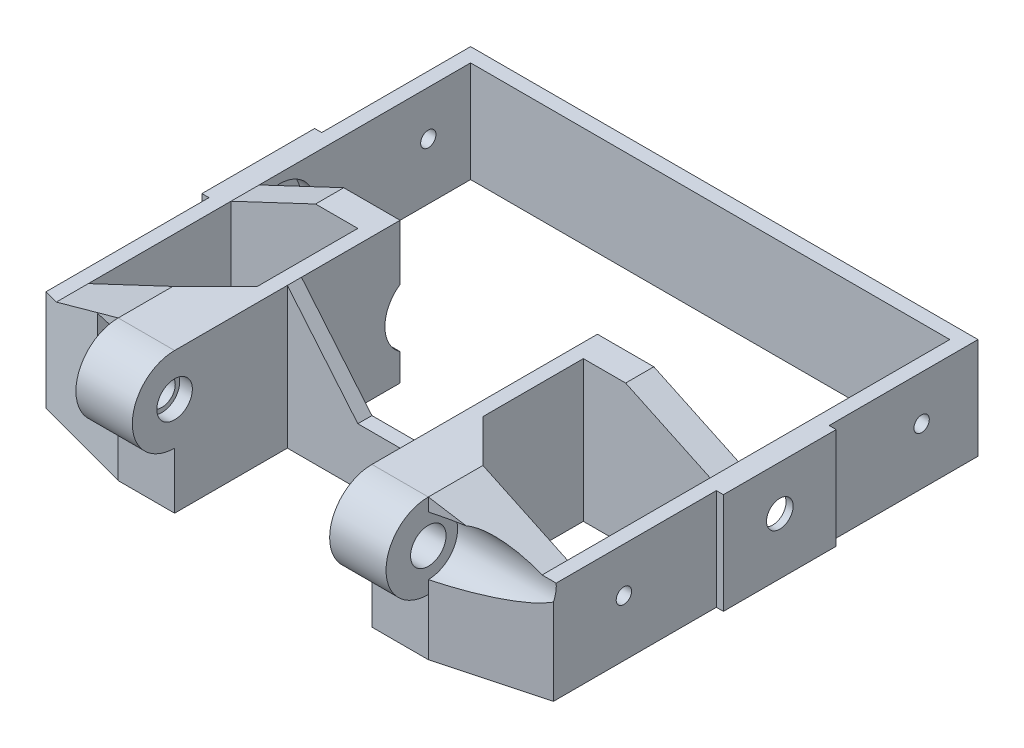
SolidWorks part; units mm, degrees
material "ABS"
ref_plane "Front Plane" through (0, 0, 0) normal (0, 0, 1) x (1, 0, 0)
ref_plane "Top Plane" through (0, 0, 0) normal (0, 1, 0) x (1, 0, 0)
ref_plane "Right Plane" through (0, 0, 0) normal (1, 0, 0) x (0, 0, -1)
sketch "Sketch1" plane through (0, 0, 0) normal (0, 0, 1) x (1, 0, 0)
  line L0 (-22.225, 0) -> (22.225, 0) construction
  line L1 (-22.225, 0) -> (-34.925, 0)
  line L2 (-22.225, 0) -> (-22.225, 9.525)
  line L3 (-22.225, 9.525) -> (-34.925, 9.525)
  line L4 (-34.925, 0) -> (-34.925, 9.525)
  line L5 (22.225, 0) -> (34.925, 0)
  line L6 (22.225, 0) -> (22.225, 9.525)
  line L7 (22.225, 9.525) -> (34.925, 9.525)
  line L8 (34.925, 0) -> (34.925, 9.525)
  dimension "D1" = 44.45
  dimension "D2" = 9.525
  dimension "D3" = 12.7
revolve "Revolve1" add sketch "Sketch1" angle 360 about L0
sketch "Sketch2" plane through (0, 0, 0) normal (0, 1, 0) x (1, 0, 0)
  line L1 (-34.925, 0) -> (-57.15, 5.9552)
  line L2 (-34.925, 9.525) -> (-34.925, -9.525) construction
  line L3 (-57.15, 5.9552) -> (-57.15, 101.6)
  line L4 (-57.15, 101.6) -> (57.15, 101.6)
  line L5 (57.15, 101.6) -> (57.15, 5.9552)
  line L6 (57.15, 5.9552) -> (34.925, 0)
  line L7 (34.925, -9.525) -> (34.925, 9.525) construction
  line L8 (34.925, 0) -> (22.225, 0)
  line L9 (22.225, 9.525) -> (22.225, -9.525) construction
  line L10 (22.225, 0) -> (22.225, 25.4)
  line L11 (22.225, 25.4) -> (-22.225, 25.4)
  line L12 (-22.225, 25.4) -> (-22.225, 0)
  line L13 (-22.225, -9.525) -> (-22.225, 9.525) construction
  line L14 (-22.225, 0) -> (-34.925, 0)
  line L15 (-22.225, 50.8) -> (-53.975, 50.8)
  line L16 (-22.225, 28.575) -> (22.225, 28.575)
  line L17 (-22.225, 28.575) -> (-22.225, 98.425)
  line L18 (-22.225, 98.425) -> (22.225, 98.425)
  line L19 (22.225, 28.575) -> (22.225, 98.425)
  line L20 (-53.975, 98.425) -> (-25.4, 98.425)
  line L21 (-53.975, 98.425) -> (-53.975, 12.3052)
  line L22 (-53.975, 12.3052) -> (-25.4, 12.3052)
  line L23 (-25.4, 98.425) -> (-25.4, 12.3052)
  line L24 (25.4, 98.425) -> (53.975, 98.425)
  line L25 (25.4, 98.425) -> (25.4, 12.3052)
  line L26 (25.4, 12.3052) -> (53.975, 12.3052)
  line L27 (53.975, 98.425) -> (53.975, 12.3052)
  line L28 (-25.4, 44.45) -> (-53.975, 44.45)
  line L29 (22.225, 50.8) -> (53.975, 50.8)
  line L30 (25.4, 44.45) -> (53.975, 44.45)
  line L31 (-25.4, 98.425) -> (-22.225, 98.425)
  line L32 (22.225, 98.425) -> (25.4, 98.425)
  line L33 (25.4, 98.425) -> (23.8524, 98.3686)
  point P24 (-28.575, 0)
  dimension "D1" = 25.4
  dimension "D2" = 101.6
  dimension "D3" = 75
  dimension "D4" = 114.3
  dimension "D5" = 3.175
  dimension "D6" = 3.175
  dimension "D7" = 3.175
  dimension "D8" = 3.175
  dimension "D9" = 3.175
  dimension "D10" = 6.35
  dimension "D11" = 6.35
  dimension "D12" = 47.625
extrude "Boss-Extrude1" add sketch "Sketch2" along normal blind 9.525 and the other way blind 22.225 contours L14 L12 L11 L10 L8 L6 L5 L4 L3 L1 L19 L16 L17 L18 L20 L23 L22 L21 L24 L27 L26 L25 | L28 L23 L15 L21 | L25 L30 L27 L29
sketch "Sketch3" plane through (0, 0, -101.6) normal (0, 0, -1) x (-1, 0, 0)
  line L0 (-53.975, 0.5447) -> (-34.925, 9.525)
  line L2 (57.15, 9.525) -> (-57.15, 9.525) construction
  line L3 (-34.925, 9.525) -> (34.925, 9.525)
  line L4 (34.925, 9.525) -> (53.975, 0.5447)
  line L6 (-53.975, -22.225) -> (-53.975, 9.525) construction
  line L7 (-53.975, 0.5447) -> (-78.3608, 0.5447)
  line L8 (53.975, -22.225) -> (53.975, 9.525) construction
  line L9 (53.975, 0.5447) -> (73.1372, 0.5447)
  dimension "D1" = 9.525
extrude "Cut-Extrude1" cut sketch "Sketch3" against normal through all and the other way through all
chamfer "Chamfer1" distance 9.525 angle 45 2 edges at (-25.4, -6.35, -12.3052) (25.4, -6.35, -12.3052)
ref_axis "Axis1" through (116.4289, 0, 0) along (-1, 0, 0)
sketch "Sketch11" plane through (0, 0.5447, 0) normal (0, 1, 0) x (1, 0, 0)
  line L1 (-57.15, 101.6) -> (86.0291, 101.6)
  line L2 (-57.15, 101.6) -> (-57.15, 89.1112)
  line L3 (-57.15, 89.1112) -> (86.0291, 89.1112)
  line L4 (86.0291, 101.6) -> (86.0291, 89.1112)
extrude "Cut-Extrude5" cut sketch "Sketch11" along normal through all
sketch "Sketch5" plane through (0, 0, 0) normal (0, 1, 0) x (1, 0, 0)
  line L0 (116.4289, 0) -> (-93.7664, 0) construction
  line L1 (-25.075, 0) -> (34.925, 0)
  line L2 (-25.075, 0) -> (-25.075, -4)
  line L3 (-25.075, -4) -> (34.925, -4)
  line L4 (34.925, 0) -> (34.925, -4)
  line L6 (-34.925, 0) -> (-34.925, -9.525) construction
  line L10 (-25.075, 0) -> (-34.925, 0)
  line L11 (-25.075, 0) -> (-25.075, -3)
  line L12 (-25.075, -3) -> (-34.925, -3)
  line L13 (-34.925, 0) -> (-34.925, -3)
  line L14 (-34.925, 0) -> (-41.275, 0)
  line L15 (-34.925, 0) -> (-34.925, -6.604)
  line L16 (-34.925, -6.604) -> (-41.275, -6.604)
  line L17 (-41.275, 0) -> (-41.275, -6.604)
  line L18 (34.925, 0) -> (73.3497, 0)
  line L19 (34.925, 0) -> (34.925, -6.604)
  line L20 (34.925, -6.604) -> (73.3497, -6.604)
  line L21 (73.3497, 0) -> (73.3497, -6.604)
  point P6 (33.6539, 0)
  point P7 (33.3375, 0)
  point P8 (73.3497, -7.62)
  point P18 (22.4886, -4)
  point P19 (33.3375, 0)
  point P22 (-33.412, -2.5)
  point P23 (-35.2585, 0)
  point P24 (-35.0967, 0)
  point P25 (-35.416, 0)
  point P26 (-34.925, -6.604)
  dimension "D1" = 4
  dimension "D2" = 3
  dimension "D3" = 6.604
  dimension "D4" = 60
  dimension "D5" = 6.35
revolve "Cut-Revolve1" cut sketch "Sketch5" angle 360 about axis through (116.4289, 0, 0) along (-1, 0, 0)
sketch "Sketch6" plane through (-57.15, 0, 0) normal (-1, 0, 0) x (0, 0, 1)
  line L0 (-88.9, -9.525) -> (-21.8302, -9.525) construction
  line L1 (-101.6, -22.225) -> (-101.6, 0.5447) construction
  line L2 (-5.9552, -22.225) -> (-5.9552, 0.5447) construction
  line L3 (-5.9552, -22.225) -> (-101.6, -22.225) construction
  circle A0 centre (-88.9, -9.525) radius 1.7272
  circle A1 centre (-21.8302, -9.525) radius 1.7272
  circle A2 centre (-21.8302, -9.525) radius 17.4625 construction
  circle A3 centre (-88.9, -9.525) radius 17.4625 construction
  circle A4 centre (-55.3651, -9.525) radius 8
  dimension "D1" = 34.925
  dimension "D2" = 16
  dimension "D3" = 3.4544
  dimension "D4" = 12.7
  dimension "D5" = 15.875
  dimension "D6" = 12.7
extrude "Cut-Extrude3" cut sketch "Sketch6" against normal up to next
sketch "Sketch7" plane through (-57.15, 0, 0) normal (-1, 0, 0) x (0, 0, 1)
  line L1 (-68.0651, 0.5447) -> (-42.6651, 0.5447)
  line L2 (-68.0651, 0.5447) -> (-68.0651, -22.225)
  line L3 (-68.0651, -22.225) -> (-42.6651, -22.225)
  line L4 (-42.6651, 0.5447) -> (-42.6651, -22.225)
  line L5 (-5.9552, -22.225) -> (-101.6, -22.225) construction
  line L7 (-101.6, 0.5447) -> (-5.9552, 0.5447) construction
  point P4 (0, 0)
  point P8 (-55.3651, -22.225)
  point P9 (-55.3651, -9.525)
  point P10 (0, 0)
  point P12 (0, 0)
  dimension "D1" = 25.4
extrude "Boss-Extrude2" add sketch "Sketch7" along normal blind 1.5875
sketch "Sketch8" plane through (-58.7375, 0, 0) normal (-1, 0, 0) x (0, 0, 1)
  circle A0 centre (-55.3651, -9.525) radius 3
  dimension "D1" = 6
extrude "Cut-Extrude4" cut sketch "Sketch8" against normal up to next
mirror "Mirror1" about plane through (0, 0, 0) normal (1, 0, 0) of "Cut-Extrude4", "Boss-Extrude2", "Cut-Extrude3"
sketch "Sketch12" plane through (0, 0, -25.4) normal (0, 0, 1) x (1, 0, 0)
  line L0 (-22.225, 9.525) -> (-6.35, -9.525)
  line L1 (-6.35, -9.525) -> (6.35, -9.525)
  line L2 (6.35, -9.525) -> (22.225, 9.525)
  line L3 (34.925, 9.525) -> (22.225, 9.525) construction
  line L4 (22.225, 9.525) -> (-22.225, 9.525) construction
  point P3 (0, 0)
  point P10 (0, -9.525)
  dimension "D1" = 12.7
  dimension "D2" = 19.05
extrude "Cut-Extrude6" cut sketch "Sketch12" against normal blind 12.7 and the other way through all
